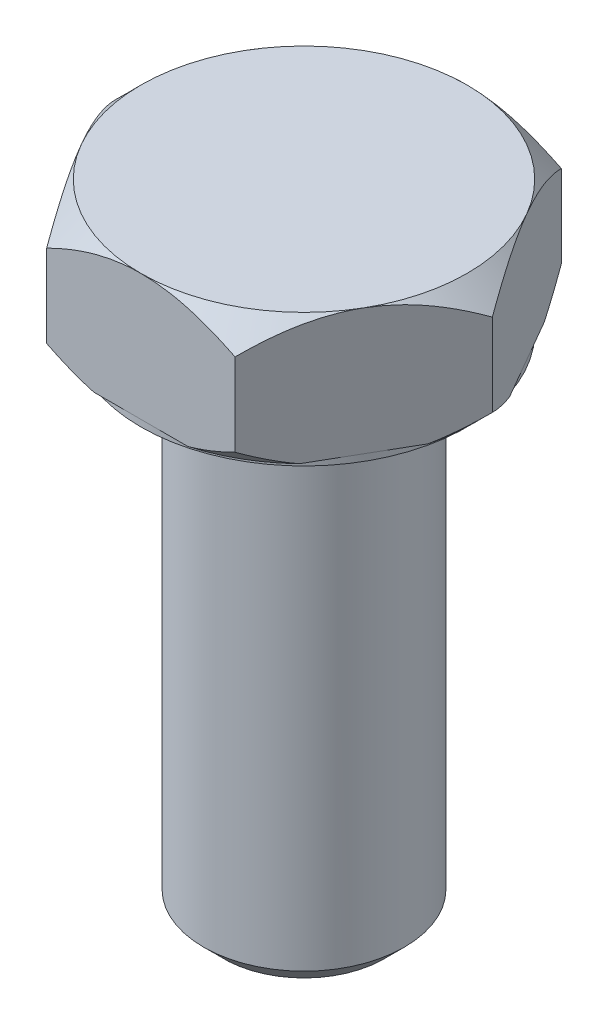
SolidWorks part; units mm, degrees
material "Cast Stainless Steel"
ref_plane "Front Plane" through (0, 0, 0) normal (0, 0, 1) x (1, 0, 0)
ref_plane "Top Plane" through (0, 0, 0) normal (0, 1, 0) x (1, 0, 0)
ref_plane "Right Plane" through (0, 0, 0) normal (1, 0, 0) x (0, 0, -1)
sketch "Sketch1" plane through (0, 0, 0) normal (0, 1, 0) x (1, 0, 0)
  line L0 (0, 0) -> (7.5056, 0) construction
  line L1 (7.5056, 0) -> (3.7528, 6.5)
  line L2 (3.7528, 6.5) -> (-3.7528, 6.5)
  line L3 (-3.7528, 6.5) -> (-7.5056, 0)
  line L4 (-7.5056, 0) -> (-3.7528, -6.5)
  line L5 (-3.7528, -6.5) -> (3.7528, -6.5)
  line L6 (3.7528, -6.5) -> (7.5056, 0)
  circle A0 centre (0, 0) radius 6.5 construction
  dimension "D1" = 13
extrude "Boss-Extrude1" add sketch "Sketch1" against normal blind 5.3
sketch "Sketch4" plane through (0, 0, 0) normal (1, 0, 0) x (0, 0, -1)
  line L0 (-6.5, 0) -> (-8.15, 0)
  line L1 (-8.15, 0) -> (-8.15, -1.65)
  line L2 (-8.15, -1.65) -> (-6.5, 0)
  line L3 (-6.5, -2.65) -> (6.5, -2.65) construction
  line L4 (-8.15, -3.65) -> (-6.5, -5.3)
  line L5 (-8.15, -5.3) -> (-8.15, -3.65)
  line L6 (-6.5, -5.3) -> (-8.15, -5.3)
  line L7 (0, 0) -> (0, -2.65) construction
  dimension "D1" = 45
  dimension "D2" = 2.65
  dimension "D3" = 1.65
  dimension "D4" = 13
revolve "Cut-Revolve1" cut sketch "Sketch4" angle 360 about L7
sketch "Sketch2" plane through (0, -5.3, 0) normal (0, -1, 0) x (1, 0, 0)
  circle A0 centre (0, 0) radius 6.5
  dimension "D1" = 13
extrude "Cut-Extrude1" cut sketch "Sketch2" against normal blind 0.265 flip side to cut
sketch "Sketch3" plane through (0, -5.3, 0) normal (0, -1, 0) x (1, 0, 0)
  circle A0 centre (0, 0) radius 4
  dimension "D1" = 8
extrude "Boss-Extrude2" add sketch "Sketch3" along normal blind 20
chamfer "Chamfer1" distance 0.8 angle 45 1 edges at (0, -25.3, -4)
equation "\"k\"= 5.3"
equation "\"e\"= 14.38"
equation "\"S\"= 13"
equation "\"L\"= 20"
equation "\"D1@Sketch1\"=\"S\""
equation "\"D1@Boss-Extrude1\"=\"k\""
equation "\"D1@Sketch2\"=\"S\""
equation "\"D1@Cut-Extrude1\"=\"k\"/20"
equation "\"d\"= 8"
equation "\"D1@Sketch3\"=\"d\""
equation "\"D1@Boss-Extrude2\"=\"L\""
equation "\"D2@Sketch4\"=\"k\"/2"
equation "\"D3@Sketch4\"=\"D2@Sketch4\"-1"
equation "\"D4@Sketch4\"=\"S\""
equation "\"D1@Chamfer1\"=\"d\"/10"
